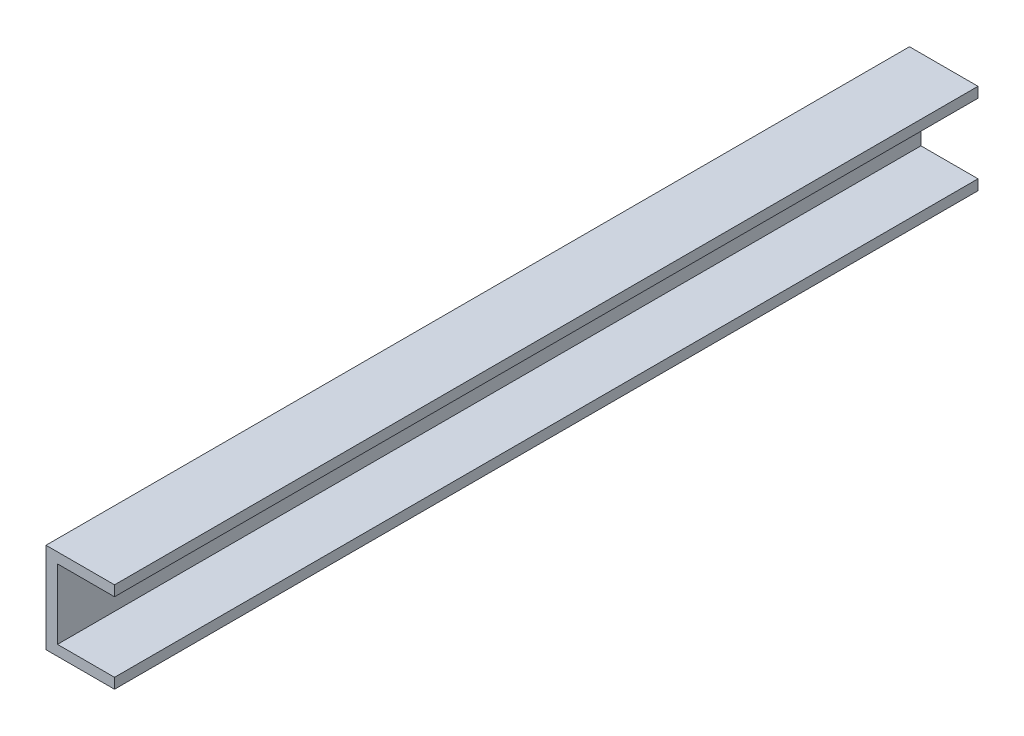
SolidWorks part; units mm, degrees
ref_plane "Front Plane" through (0, 0, 0) normal (0, 0, 1) x (1, 0, 0)
ref_plane "Top Plane" through (0, 0, 0) normal (0, 1, 0) x (1, 0, 0)
ref_plane "Right Plane" through (0, 0, 0) normal (1, 0, 0) x (0, 0, -1)
sketch "Sketch1" plane through (0, 0, 0) normal (0, 0, 1) x (1, 0, 0)
  line L0 (0, 35) -> (0, -35)
  line L1 (0, -35) -> (53.0172, -35)
  line L2 (53.0172, -35) -> (53.0172, -26.9745)
  line L3 (53.0172, -26.9745) -> (8.877, -26.9745)
  line L4 (8.877, -26.9745) -> (8.877, 26.9745)
  line L5 (8.877, 26.9745) -> (53.0172, 26.9745)
  line L6 (53.0172, 26.9745) -> (53.0172, 35)
  line L7 (53.0172, 35) -> (0, 35)
  point P4 (0, 0)
  dimension "D1" = 70
extrude "Boss-Extrude1" add sketch "Sketch1" along normal blind 668.02
